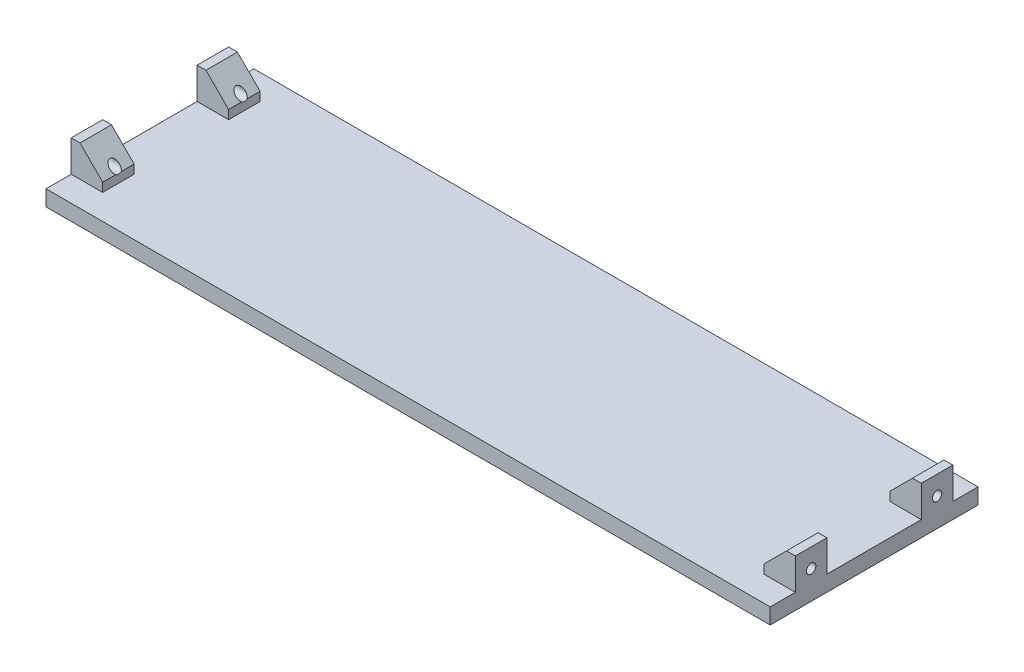
SolidWorks part; units mm, degrees
ref_plane "Front Plane" through (0, 0, 0) normal (0, 0, 1) x (1, 0, 0)
ref_plane "Top Plane" through (0, 0, 0) normal (0, 1, 0) x (1, 0, 0)
ref_plane "Right Plane" through (0, 0, 0) normal (1, 0, 0) x (0, 0, -1)
sketch "Sketch1" plane through (0, 0, 0) normal (0, 1, 0) x (1, 0, 0)
  line L1 (0, -33) -> (230, -33)
  line L2 (0, -33) -> (0, 33)
  line L3 (0, 33) -> (230, 33)
  line L4 (230, -33) -> (230, 33)
  point P4 (71.092, 32.1187)
  dimension "D1" = 66
  dimension "D2" = 230
extrude "Boss-Extrude1" add sketch "Sketch1" along normal blind 5
sketch "Sketch2" plane through (0, 5, 0) normal (0, 1, 0) x (1, 0, 0)
  line L0 (0, 33) -> (0, -33) construction
  line L1 (0, -25) -> (10, -25)
  line L2 (0, -25) -> (0, -15)
  line L3 (0, -15) -> (10, -15)
  line L4 (10, -25) -> (10, -15)
  line L14 (220, -25) -> (220, -15)
  line L19 (220, -25) -> (230, -25)
  line L20 (230, -25) -> (230, -15)
  line L21 (220, -15) -> (230, -15)
  line L22 (220, 15) -> (220, 25)
  line L23 (220, 15) -> (230, 15)
  line L24 (230, 15) -> (230, 25)
  line L25 (220, 25) -> (230, 25)
  line L26 (0, 15) -> (0, 25)
  line L27 (0, 15) -> (10, 15)
  line L28 (10, 15) -> (10, 25)
  line L29 (0, 25) -> (10, 25)
  dimension "D1" = 10
  dimension "D2" = 10
  dimension "D3" = 15
  dimension "D4" = 2
  dimension "D5" = 2
extrude "Boss-Extrude2" add sketch "Sketch2" along normal blind 10
sketch "Sketch3" plane through (230, 0, 0) normal (1, 0, 0) x (0, 0, -1)
  line L0 (-20, 15) -> (-20, 2.7644) construction
  line L1 (-25, 15) -> (-15, 15) construction
  line L2 (20, 15) -> (20, 4.2527) construction
  line L3 (15, 15) -> (25, 15) construction
  line L4 (-15, 5) -> (15, 5) construction
  circle A0 centre (-20, 9) radius 1.5
  circle A1 centre (20, 9) radius 1.5
  point P12 (20, 6.7558)
  point P13 (-20, 7.8383)
  dimension "D1" = 3
  dimension "D2" = 3
  dimension "D3" = 4
  dimension "D4" = 4
extrude "Cut-Extrude1" cut sketch "Sketch3" against normal through all
sketch "Sketch4" plane through (0, 0, -25) normal (0, 0, -1) x (-1, 0, 0)
  line L0 (-227.2, 15) -> (-220, 7.8)
  line L2 (-220, 15) -> (-220, 5) construction
  line L3 (-115, 5) -> (-115, 18.6765) construction
  line L6 (-230, 5) -> (0, 5) construction
  line L7 (-227.2, 15) -> (-220, 15)
  line L8 (-220, 15) -> (-220, 7.8)
  line L9 (-2.8, 15) -> (-10, 15)
  line L10 (-2.8, 15) -> (-10, 7.8)
  line L11 (-10, 15) -> (-10, 7.8)
  dimension "D1" = 2.8
  dimension "D2" = 2.8
extrude "Cut-Extrude2" cut sketch "Sketch4" against normal through all
